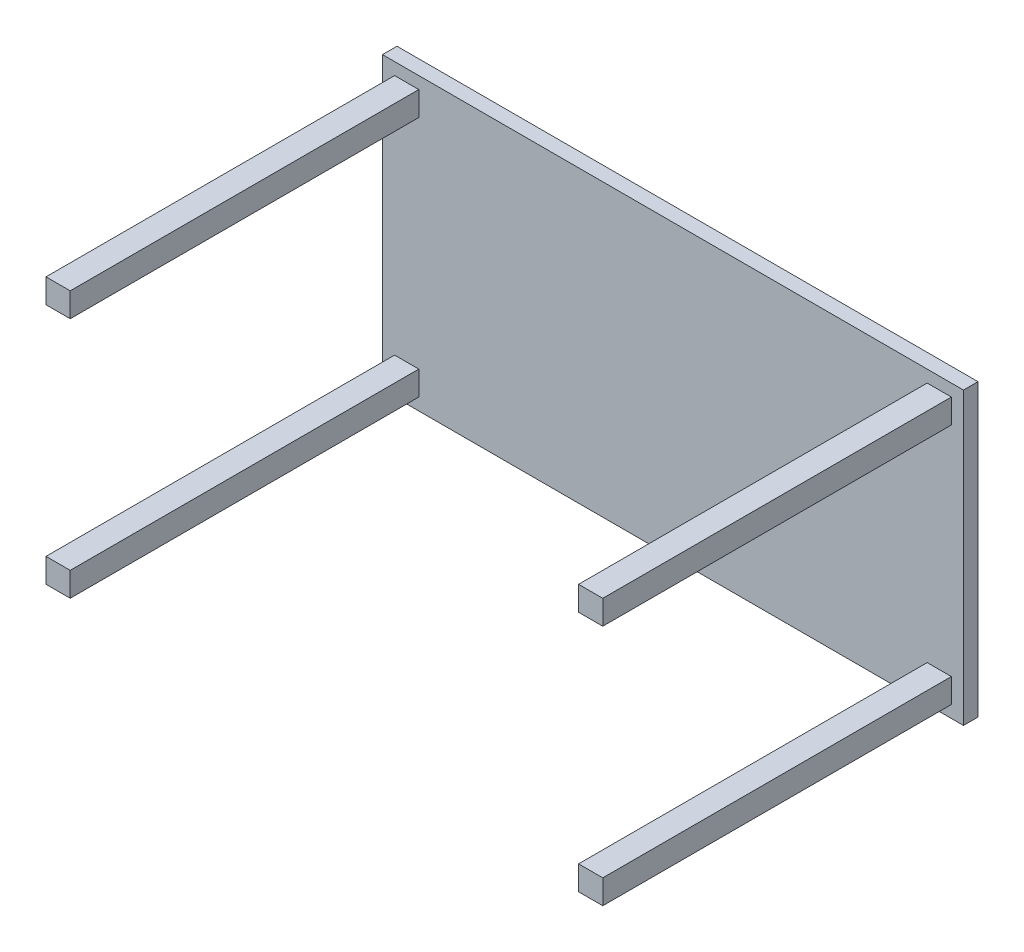
SolidWorks part; units mm, degrees
ref_plane "前视基准面" through (0, 0, 0) normal (0, 0, 1) x (1, 0, 0)
ref_plane "上视基准面" through (0, 0, 0) normal (0, 1, 0) x (1, 0, 0)
ref_plane "右视基准面" through (0, 0, 0) normal (1, 0, 0) x (0, 0, -1)
other "Configuration Table"
sketch "草图1" plane through (0, 0, 0) normal (0, 0, 1) x (1, 0, 0)
  line L1 (-600, -300) -> (600, -300)
  line L2 (-600, -300) -> (-600, 300)
  line L3 (-600, 300) -> (600, 300)
  line L4 (600, -300) -> (600, 300)
  line L5 (-600, -300) -> (600, 300) construction
  line L6 (-600, 300) -> (600, -300) construction
  point P0 (0, 0)
extrude "凸台-拉伸1" add sketch "草图1" along normal blind 30
sketch "草图2" plane through (0, 0, 0) normal (0, 0, 1) x (1, 0, 0)
  line L1 (-575, -275) -> (-525, -275)
  line L2 (-575, -275) -> (-575, -225)
  line L3 (-575, -225) -> (-525, -225)
  line L4 (-525, -275) -> (-525, -225)
  line L5 (-575, -275) -> (-525, -225) construction
  line L6 (-575, -225) -> (-525, -275) construction
  point P0 (-550, -250)
extrude "凸台-拉伸2" add sketch "草图2" along normal blind 750
sketch "草图3" plane through (0, 0, 0) normal (0, 0, 1) x (1, 0, 0)
  line L1 (525, -275) -> (575, -275)
  line L2 (525, -275) -> (525, -225)
  line L3 (525, -225) -> (575, -225)
  line L4 (575, -275) -> (575, -225)
  line L5 (525, -275) -> (575, -225) construction
  line L6 (525, -225) -> (575, -275) construction
  point P0 (550, -250)
extrude "凸台-拉伸3" add sketch "草图3" along normal blind 750
sketch "草图4" plane through (0, 0, 0) normal (0, 0, 1) x (1, 0, 0)
  line L1 (-575, 225) -> (-525, 225)
  line L2 (-575, 225) -> (-575, 275)
  line L3 (-575, 275) -> (-525, 275)
  line L4 (-525, 225) -> (-525, 275)
  line L5 (-575, 225) -> (-525, 275) construction
  line L6 (-575, 275) -> (-525, 225) construction
  point P0 (-550, 250)
extrude "凸台-拉伸4" add sketch "草图4" along normal blind 750
sketch "草图5" plane through (0, 0, 0) normal (0, 0, 1) x (1, 0, 0)
  line L1 (525, 225) -> (575, 225)
  line L2 (525, 225) -> (525, 275)
  line L3 (525, 275) -> (575, 275)
  line L4 (575, 225) -> (575, 275)
  line L5 (525, 225) -> (575, 275) construction
  line L6 (525, 275) -> (575, 225) construction
  point P0 (550, 250)
extrude "凸台-拉伸5" add sketch "草图5" along normal blind 750
